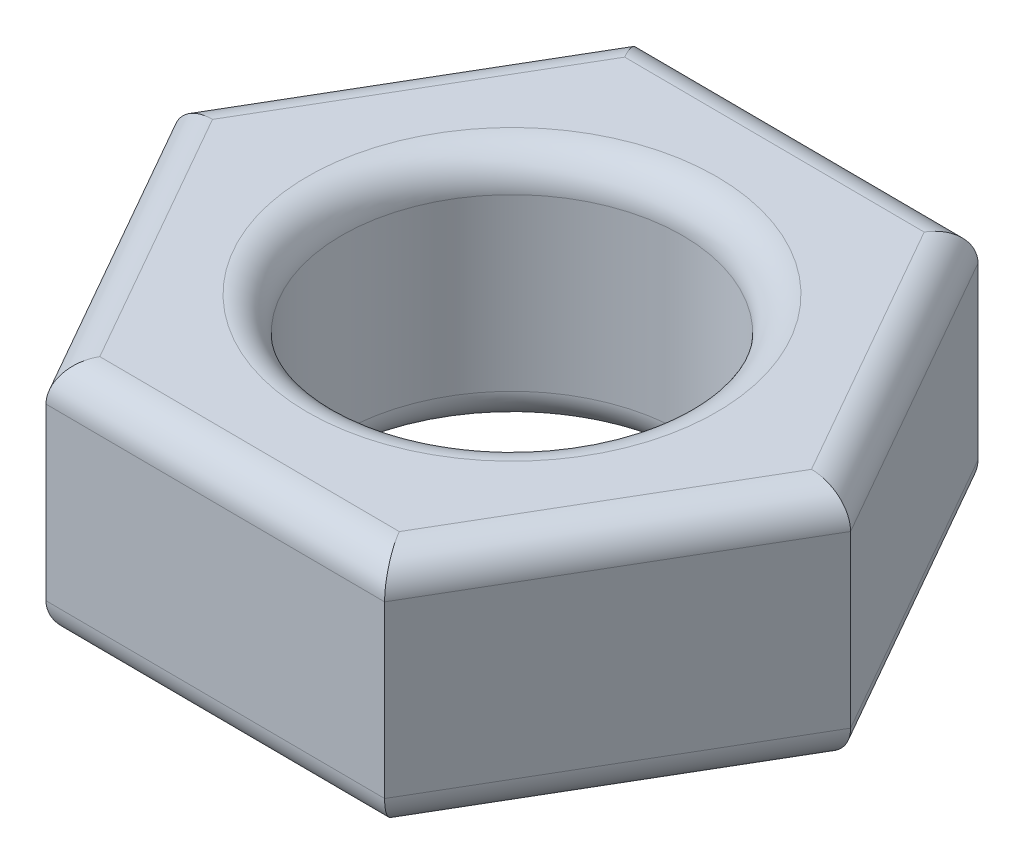
SolidWorks part; units mm, degrees
ref_plane "Front" through (0, 0, 0) normal (0, 0, 1) x (1, 0, 0)
ref_plane "Top" through (0, 0, 0) normal (0, 1, 0) x (1, 0, 0)
ref_plane "Right" through (0, 0, 0) normal (1, 0, 0) x (0, 0, -1)
sketch "Sketch1" plane through (0, 0, 0) normal (0, 1, 0) x (1, 0, 0)
  line L1 (10, 10) -> (-10, 10)
  line L2 (10, 10) -> (10, -10)
  line L3 (10, -10) -> (-10, -10)
  line L4 (-10, 10) -> (-10, -10)
  line L5 (10, 10) -> (-10, -10) construction
  line L6 (10, -10) -> (-10, 10) construction
  point P0 (0, 0)
  dimension "D1" = 20
  dimension "D2" = 20
extrude "Boss-Extrude1" add sketch "Sketch1" along normal blind 7
hole_wizard "Ø10.0mm Clearance Dowel Hole1" positions "Sketch2" profile "Sketch3" hole size "Ø10.0" standard "ANSI Metric" end condition through all
sketch "Sketch2" plane through (0, 7, 0) normal (0, 1, 0) x (1, 0, 0)
  point P0 (0, 0)
sketch "Sketch3" plane through (0, 7, 0) normal (1, 0, 0) x (0, 0, 1)
  line L0 (0, 0) -> (0, 7)
  line L1 (0, 7) -> (5, 7)
  line L2 (5, 7) -> (5, 0)
  line L5 (5, 0) -> (0, 0)
  line L11 (0, -6.35) -> (0, 107.95) construction
  dimension "Thru Hole Dia." = 10
  dimension "Thru Hole Depth" = 7
sketch "Sketch6" plane through (0, 7, 0) normal (0, 1, 0) x (1, 0, 0)
  line L0 (10, -10) -> (10, 10) construction
  line L1 (-5.0509, -8.6309) -> (4.9491, -8.6896)
  line L2 (4.9491, -8.6896) -> (10, -0.0587)
  line L3 (10, -0.0587) -> (5.0509, 8.6309)
  line L4 (5.0509, 8.6309) -> (-4.9491, 8.6896)
  line L5 (-4.9491, 8.6896) -> (-10, 0.0587)
  line L6 (-10, 0.0587) -> (-5.0509, -8.6309)
  line L9 (10, 10) -> (-10, 10)
  line L10 (10, 10) -> (10, -10)
  line L11 (10, -10) -> (-10, -10)
  line L12 (-10, 10) -> (-10, -10)
  circle A0 centre (0, 0) radius 8.6604 construction
  point P11 (7.5254, 4.2861)
  line M5 (-10, 10) -> (-10, -10)
  line M6 (-10, -10) -> (10, -10)
  line M7 (10, -10) -> (10, 10)
  line M8 (10, 10) -> (-10, 10)
  dimension "D1" = 0
  dimension "D2" = 17.3208
  dimension "D3" = 20
  dimension "D4" = 10
  dimension "D5" = 10
extrude "Cut-Extrude1" cut sketch "Sketch6" against normal through all contours L5 L4 L3 M7 M8 M5 | L6 L2 L1 M5 M6 M7
fillet "Fillet1" radius 1 14 edges at (-7.4746, 7, -4.3742) (0.0509, 7, -8.6603) (7.5254, 7, -4.2861) (7.4746, 7, 4.3742) (-0.0509, 7, 8.6603) (-7.5254, 7, 4.2861) (7.4746, 0, 4.3742) (7.5254, 0, -4.2861) (0.0509, 0, -8.6603) (-7.4746, 0, -4.3742) (-7.5254, 0, 4.2861) (-0.0509, 0, 8.6603) (0, 0, 5) (0, 7, 5)
